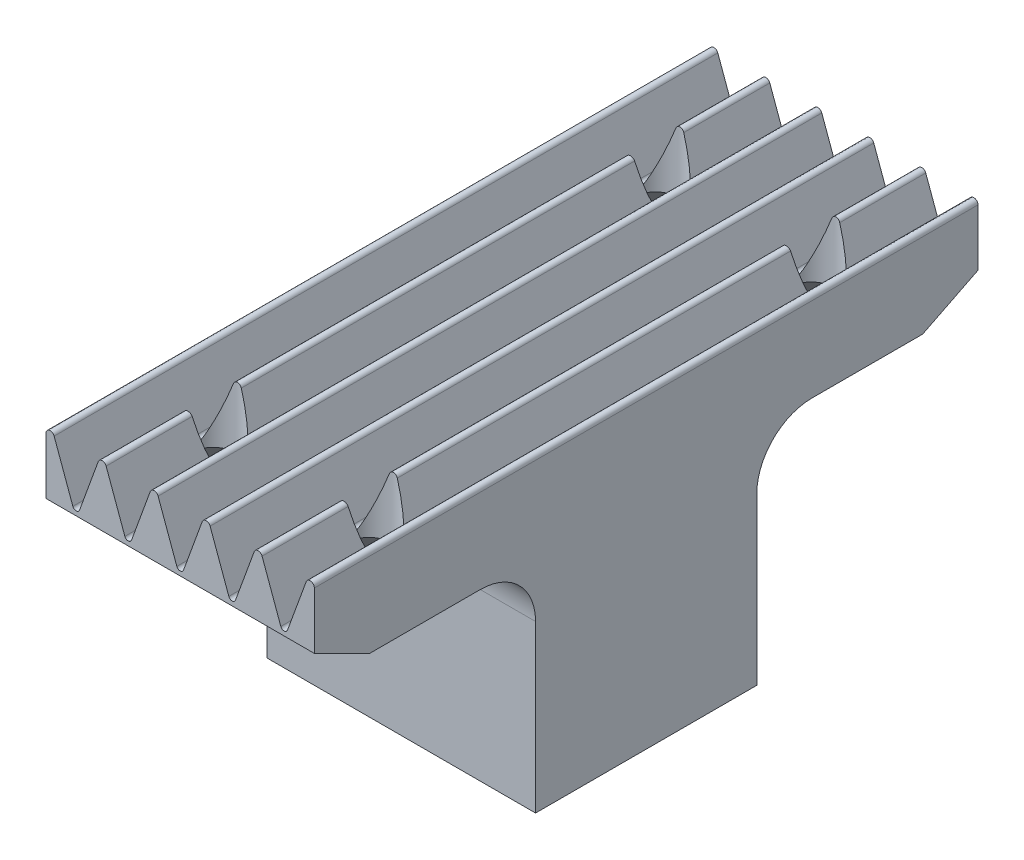
SolidWorks part; units mm, degrees
ref_plane "Спереди" through (0, 0, 0) normal (0, 0, 1) x (1, 0, 0)
ref_plane "Сверху" through (0, 0, 0) normal (0, 1, 0) x (1, 0, 0)
ref_plane "Справа" through (0, 0, 0) normal (1, 0, 0) x (0, 0, -1)
sketch "Эскиз1" plane through (0, 0, 0) normal (0, 0, 1) x (1, 0, 0)
  line L0 (0.7371, 7.75) -> (2.4293, 3.1006)
  line L1 (3.0307, 3.1006) -> (4.7229, 7.75)
  line L2 (5.4371, 7.75) -> (7.1293, 3.1006)
  line L3 (7.7307, 3.1006) -> (9.4229, 7.75)
  line L4 (10.1371, 7.75) -> (11.8293, 3.1006)
  line L5 (12.4307, 3.1006) -> (14.1229, 7.75)
  line L6 (14.8371, 7.75) -> (16.5293, 3.1006)
  line L7 (0, 0) -> (0, 7.62)
  line L8 (17.1307, 3.1006) -> (18.8229, 7.75)
  line L9 (19.5371, 7.75) -> (21.2293, 3.1006)
  line L10 (21.8307, 3.1006) -> (23.5229, 7.75)
  line L11 (0, 0) -> (24.26, 0)
  line L12 (24.26, 7.62) -> (24.26, 0)
  line L13 (7.43, 3.2101) -> (7.43, 4.2791) construction
  arc A0 (3.0307, 3.1006) -> (2.4293, 3.1006) centre (2.73, 3.2101) cw
  arc A1 (5.4371, 7.75) -> (4.7229, 7.75) centre (5.08, 7.62) ccw
  arc A2 (19.5371, 7.75) -> (18.8229, 7.75) centre (19.18, 7.62) ccw
  arc A3 (14.8371, 7.75) -> (14.1229, 7.75) centre (14.48, 7.62) ccw
  arc A4 (10.1371, 7.75) -> (9.4229, 7.75) centre (9.78, 7.62) ccw
  arc A5 (21.8307, 3.1006) -> (21.2293, 3.1006) centre (21.53, 3.2101) cw
  arc A6 (17.1307, 3.1006) -> (16.5293, 3.1006) centre (16.83, 3.2101) cw
  arc A7 (12.4307, 3.1006) -> (11.8293, 3.1006) centre (12.13, 3.2101) cw
  arc A8 (7.7307, 3.1006) -> (7.1293, 3.1006) centre (7.43, 3.2101) cw
  arc A9 (0.7371, 7.75) -> (0, 7.62) centre (0.38, 7.62) ccw
  arc A10 (24.26, 7.62) -> (23.5229, 7.75) centre (23.88, 7.62) ccw
  point P3 (2.73, 2.8901)
  point P7 (5.08, 8)
  point P35 (9.78, 8)
  point P36 (19.18, 8)
  point P42 (0.38, 8)
  point P48 (23.88, 8)
  dimension "D1" = 0.32
  dimension "D2" = 0.38
  dimension "D4" = 0.32
  dimension "D5" = 40
  dimension "D3" = 0.38
  dimension "D7" = 0.38
  dimension "D8" = 0.38
  dimension "D6" = 4.7
  dimension "D9" = 8
  dimension "D10" = 20
extrude "Бобышка-Вытянуть1" add sketch "Эскиз1" along normal blind 60 contours A9 L7 L11 L12 A10 L10 A5 L9 A2 L8 A6 L6 A3 L5 A7 L4 A4 L3 A8 L2 A1 L1 A0 L0
sketch "Эскиз4" plane through (0, 0, 0) normal (0, -1, 0) x (1, 0, 0)
  line L2 (0, 60) -> (24.26, 60) construction
  line L3 (0, 0) -> (24.26, 0) construction
  line L4 (5.4371, 60) -> (4.7229, 60) construction
  line L5 (5.4371, 60) -> (4.7229, 60)
  line L6 (19.5371, 60) -> (18.8229, 60) construction
  line L7 (19.5371, 60) -> (18.8229, 60)
  point P0 (5.08, 50)
  point P1 (19.18, 50)
  point P2 (5.08, 10)
  point P3 (19.18, 10)
  point P9 (5.08, 60)
  point P10 (19.18, 60)
  dimension "D1" = 10
  dimension "D2" = 10
hole_wizard "Зенковка для  винта с плоской головкой M41" positions "Трехмерный эскиз1" profile "Эскиз5" countersink size "M4" standard "Ansi Metric" end condition through all
sketch3d "Трехмерный эскиз1"
  point P0 (5.08, 0, 50)
  point P3 (19.18, 0, 50)
  point P6 (19.18, 0, 10)
  point P9 (5.08, 0, 10)
sketch "Эскиз5" plane through (5.08, 0, 50) normal (1, 0, 0) x (0, 0, -1)
  line L0 (0, 0) -> (0, 8)
  line L1 (0, 8) -> (2.25, 8)
  line L2 (2.25, 8) -> (2.25, 2.45)
  line L3 (2.25, 2.45) -> (4.7, 0)
  line L5 (4.7, 0) -> (0, 0)
  line L6 (-2.25, 2.45) -> (-4.7, 0) construction
  line L11 (0, -6.35) -> (0, 107.95) construction
  dimension "Диаметр сквозного отверстия" = 4.5
  dimension "Глубина сквозного отверстия" = 8
  dimension "Диаметр передней зенковки" = 9.4
  dimension "Угол передней зенковки" = 90
sketch "Эскиз6" plane through (0, 0, 0) normal (-1, 0, 0) x (0, 0, 1)
  line L0 (40, -5) -> (40, -20)
  line L1 (60, 0) -> (0, 0) construction
  line L2 (40, -20) -> (20, -20)
  line L3 (20, -20) -> (20, -5)
  line L4 (45, 0) -> (15, 0)
  line L5 (30, -20) -> (30, 0) construction
  arc A0 (15, 0) -> (20, -5) centre (15, -5) cw
  arc A1 (45, 0) -> (40, -5) centre (45, -5) ccw
  point P10 (22.1538, 0)
  point P13 (37.5502, 0)
  point P16 (30, 0)
  dimension "D1" = 5
  dimension "D2" = 20
  dimension "D3" = 20
extrude "Бобышка-Вытянуть2" add sketch "Эскиз6" against normal through all
chamfer "Фаска1" distance 2.5 distance2 5 1 edges at (12.13, 0, 0)
chamfer "Фаска2" distance 5 distance2 2.5 1 edges at (12.13, 0, 60)
